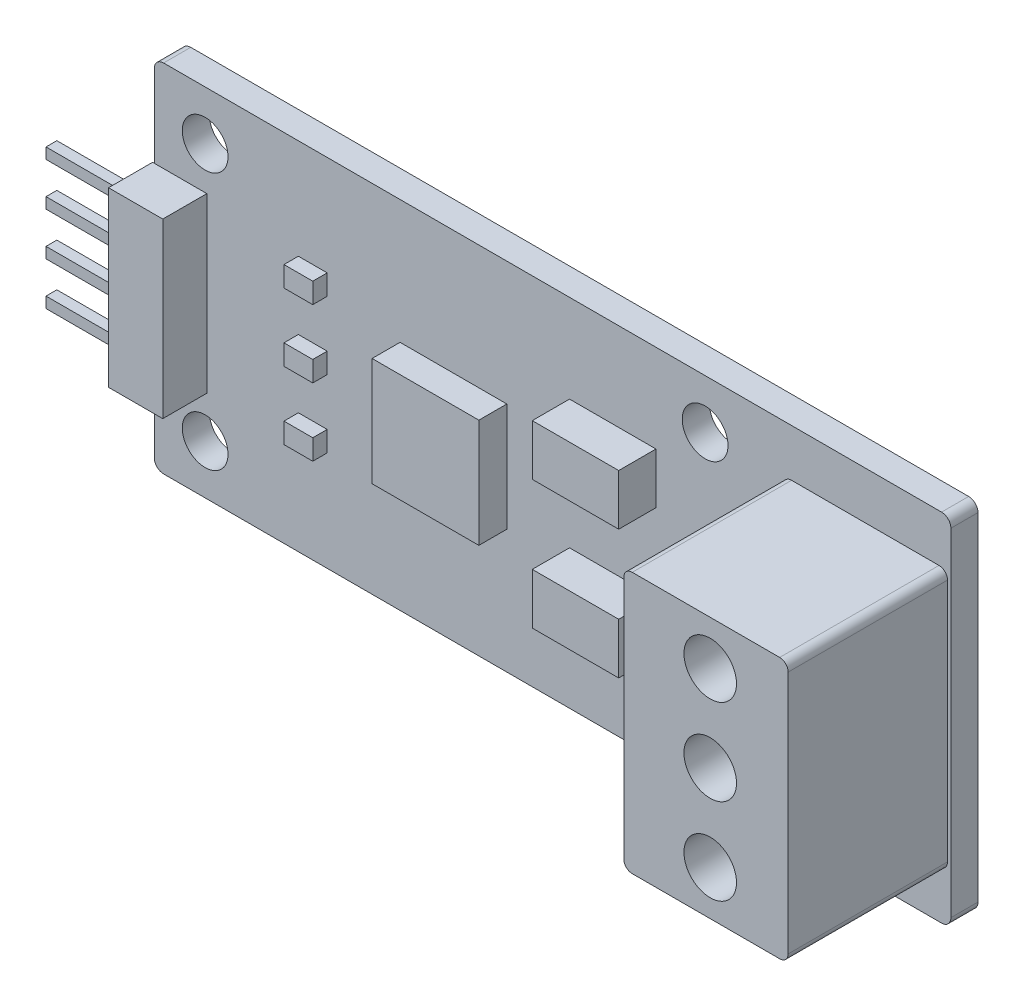
SolidWorks part; units mm, degrees
ref_plane "前视基准面" through (0, 0, 0) normal (0, 0, 1) x (1, 0, 0)
ref_plane "上视基准面" through (0, 0, 0) normal (0, 1, 0) x (1, 0, 0)
ref_plane "右视基准面" through (0, 0, 0) normal (1, 0, 0) x (0, 0, -1)
other "Configuration Table"
sketch "PCB_Overvoltage_protection_Sketch" plane through (0, 0, 0) normal (0, 0, 1) x (1, 0, 0)
  line L0 (-22.95, -10.5) -> (22.95, -10.5)
  line L1 (23.5, -9.95) -> (23.5, 9.95)
  line L2 (22.95, 10.5) -> (-22.95, 10.5)
  line L3 (-23.5, 9.95) -> (-23.5, -9.95)
  arc A0 (22.95, -10.5) -> (23.5, -9.95) centre (22.95, -9.95) ccw
  arc A1 (23.5, 9.95) -> (22.95, 10.5) centre (22.95, 9.95) ccw
  arc A2 (-22.95, 10.5) -> (-23.5, 9.95) centre (-22.95, 9.95) ccw
  arc A3 (-23.5, -9.95) -> (-22.95, -10.5) centre (-22.95, -9.95) ccw
  circle A4 centre (-20.5, -7.6) radius 1.35
  circle A5 centre (-20.5, 7.6) radius 1.35
  circle A6 centre (9, -7.6) radius 1.35
  circle A7 centre (9, 7.6) radius 1.35
extrude "PCB_Overvoltage_protection" add sketch "PCB_Overvoltage_protection_Sketch" along normal blind 1.6 separate body
sketch "TTL_2p54_Header_Sketch" plane through (0, 0, 0) normal (0, 0, 1) x (1, 0, 0)
  line L0 (-23.6, -5.1) -> (-20.4, -5.1)
  line L1 (-20.4, -5.1) -> (-20.4, 5.1)
  line L2 (-20.4, 5.1) -> (-23.6, 5.1)
  line L3 (-23.6, 5.1) -> (-23.6, -5.1)
extrude "TTL_2p54_Header" add sketch "TTL_2p54_Header_Sketch" along normal blind 2.6 from offset 1.6 separate body
sketch "Four_TTL_Pins_2p54_Sketch" plane through (0, 0, 0) normal (0, 0, 1) x (1, 0, 0)
  line L0 (-28.5, -4.13) -> (-23.6, -4.13)
  line L1 (-23.6, -4.13) -> (-23.6, -3.49)
  line L2 (-23.6, -3.49) -> (-28.5, -3.49)
  line L3 (-28.5, -3.49) -> (-28.5, -4.13)
  line L4 (-28.5, -1.59) -> (-23.6, -1.59)
  line L5 (-23.6, -1.59) -> (-23.6, -0.95)
  line L6 (-23.6, -0.95) -> (-28.5, -0.95)
  line L7 (-28.5, -0.95) -> (-28.5, -1.59)
  line L8 (-28.5, 0.95) -> (-23.6, 0.95)
  line L9 (-23.6, 0.95) -> (-23.6, 1.59)
  line L10 (-23.6, 1.59) -> (-28.5, 1.59)
  line L11 (-28.5, 1.59) -> (-28.5, 0.95)
  line L12 (-28.5, 3.49) -> (-23.6, 3.49)
  line L13 (-23.6, 3.49) -> (-23.6, 4.13)
  line L14 (-23.6, 4.13) -> (-28.5, 4.13)
  line L15 (-28.5, 4.13) -> (-28.5, 3.49)
extrude "Four_TTL_Pins_2p54" add sketch "Four_TTL_Pins_2p54_Sketch" along normal blind 0.64 from offset 2.35 separate body
sketch "Three_position_RS485_terminal_Sketch" plane through (0, 0, 0) normal (0, 0, 1) x (1, 0, 0)
  line L0 (14.1, -7.7) -> (22.8, -7.7)
  line L1 (23.3, -7.2) -> (23.3, 7.2)
  line L2 (22.8, 7.7) -> (14.1, 7.7)
  line L3 (13.6, 7.2) -> (13.6, -7.2)
  arc A0 (22.8, -7.7) -> (23.3, -7.2) centre (22.8, -7.2) ccw
  arc A1 (23.3, 7.2) -> (22.8, 7.7) centre (22.8, 7.2) ccw
  arc A2 (14.1, 7.7) -> (13.6, 7.2) centre (14.1, 7.2) ccw
  arc A3 (13.6, -7.2) -> (14.1, -7.7) centre (14.1, -7.2) ccw
extrude "Three_position_RS485_terminal" add sketch "Three_position_RS485_terminal_Sketch" along normal blind 9.4 from offset 1.6 separate body
sketch "Terminal_screw_access_Sketch" plane through (0, 0, 0) normal (0, 0, 1) x (1, 0, 0)
  circle A0 centre (18.7, -5.08) radius 1.55
  circle A1 centre (18.7, 0) radius 1.55
  circle A2 centre (18.7, 5.08) radius 1.55
extrude "Terminal_screw_access" cut sketch "Terminal_screw_access_Sketch" along normal blind 3 from offset 8
sketch "Transceiver_Sketch" plane through (0, 0, 0) normal (0, 0, 1) x (1, 0, 0)
  line L0 (-9, -3.2) -> (-2.7, -3.2)
  line L1 (-2.7, -3.2) -> (-2.7, 3.2)
  line L2 (-2.7, 3.2) -> (-9, 3.2)
  line L3 (-9, 3.2) -> (-9, -3.2)
extrude "Transceiver" add sketch "Transceiver_Sketch" along normal blind 1.65 from offset 1.6 separate body
sketch "TVS_A_Sketch" plane through (0, 0, 0) normal (0, 0, 1) x (1, 0, 0)
  line L0 (1, -5.3) -> (6.1, -5.3)
  line L1 (6.1, -5.3) -> (6.1, -2.3)
  line L2 (6.1, -2.3) -> (1, -2.3)
  line L3 (1, -2.3) -> (1, -5.3)
extrude "TVS_A" add sketch "TVS_A_Sketch" along normal blind 2.2 from offset 1.6 separate body
sketch "TVS_B_Sketch" plane through (0, 0, 0) normal (0, 0, 1) x (1, 0, 0)
  line L0 (1, 2.3) -> (6.1, 2.3)
  line L1 (6.1, 2.3) -> (6.1, 5.3)
  line L2 (6.1, 5.3) -> (1, 5.3)
  line L3 (1, 5.3) -> (1, 2.3)
extrude "TVS_B" add sketch "TVS_B_Sketch" along normal blind 2.2 from offset 1.6 separate body
sketch "Status_LEDs_Sketch" plane through (0, 0, 0) normal (0, 0, 1) x (1, 0, 0)
  line L0 (-15, -4.6) -> (-13.3, -4.6)
  line L1 (-13.3, -4.6) -> (-13.3, -3.4)
  line L2 (-13.3, -3.4) -> (-15, -3.4)
  line L3 (-15, -3.4) -> (-15, -4.6)
  line L4 (-15, -0.6) -> (-13.3, -0.6)
  line L5 (-13.3, -0.6) -> (-13.3, 0.6)
  line L6 (-13.3, 0.6) -> (-15, 0.6)
  line L7 (-15, 0.6) -> (-15, -0.6)
  line L8 (-15, 3.4) -> (-13.3, 3.4)
  line L9 (-13.3, 3.4) -> (-13.3, 4.6)
  line L10 (-13.3, 4.6) -> (-15, 4.6)
  line L11 (-15, 4.6) -> (-15, 3.4)
extrude "Status_LEDs" add sketch "Status_LEDs_Sketch" along normal blind 0.85 from offset 1.6 separate body
